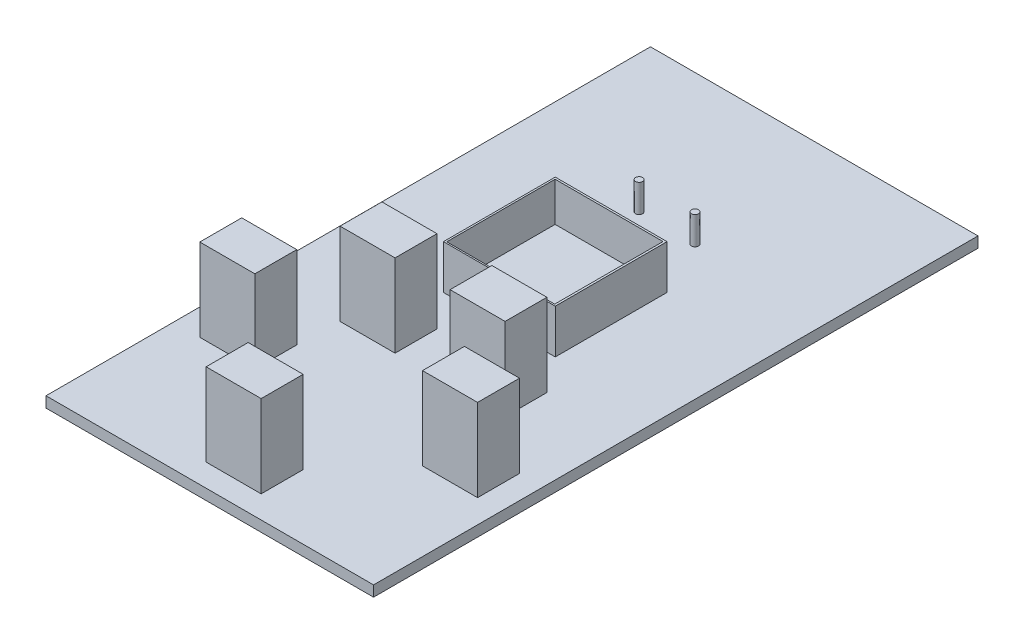
SolidWorks part; units mm, degrees
ref_plane "Front Plane" through (0, 0, 0) normal (0, 0, 1) x (1, 0, 0)
ref_plane "Top Plane" through (0, 0, 0) normal (0, 1, 0) x (1, 0, 0)
ref_plane "Right Plane" through (0, 0, 0) normal (1, 0, 0) x (0, 0, -1)
sketch "Sketch1" plane through (0, 0, 0) normal (0, 1, 0) x (1, 0, 0)
  line L1 (0, 0) -> (101.6, 0)
  line L2 (0, 0) -> (0, 101.6)
  line L3 (0, 101.6) -> (101.6, 101.6)
  line L4 (101.6, 0) -> (101.6, 101.6)
  dimension "D1" = 101.6
  dimension "D2" = 101.6
extrude "Boss-Extrude1" add sketch "Sketch1" along normal blind 39.9999
sketch "Sketch2" plane through (0, 39.9999, 0) normal (0, 1, 0) x (1, 0, 0)
  line L1 (1.6077, 99.8575) -> (99.7228, 99.8575)
  line L2 (1.6077, 99.8575) -> (1.6077, 1.3382)
  line L3 (1.6077, 1.3382) -> (99.7228, 1.3382)
  line L4 (99.7228, 99.8575) -> (99.7228, 1.3382)
extrude "Cut-Extrude1" cut sketch "Sketch2" against normal blind 35.56
sketch "Sketch3" plane through (0, 0, 0) normal (0, -1, 0) x (1, 0, 0)
  line L0 (101.6, -101.6) -> (50.8, -101.6) construction
  line L1 (101.6, -101.6) -> (0, -101.6) construction
  line L2 (50.8, -101.6) -> (50.8, 50.8) construction
  line L3 (50.8, 50.8) -> (25.8, 50.8) construction
  line L4 (50.8, 50.8) -> (75.8, 50.8) construction
  line L5 (25.8, 50.8) -> (25.8, 69.8) construction
  line L6 (75.8, 50.8) -> (75.8, 69.8) construction
  line L7 (50.8, 50.8) -> (50.8, 127) construction
  line L8 (75.8, 69.8) -> (125.7999, 69.8)
  line L9 (75.8, 69.8) -> (75.8, 31.8001)
  line L10 (75.8, 31.8001) -> (125.7999, 31.8001)
  line L11 (125.7999, 69.8) -> (125.7999, 31.8001)
  line L12 (25.8, 69.8) -> (-24.238, 69.8)
  line L13 (25.8, 69.8) -> (25.8, 31.7)
  line L14 (25.8, 31.7) -> (-24.238, 31.7)
  line L15 (-24.238, 69.8) -> (-24.238, 31.7)
  line L16 (50.8, 127) -> (50.8, 203.2) construction
  line L17 (50.8, 127) -> (-25.4, 127) construction
  line L18 (50.8, 127) -> (127, 127) construction
  line L19 (127, 127) -> (127, 146.05) construction
  line L20 (-25.4, 127) -> (-25.4, 146.05) construction
  line L21 (50.8, 203.2) -> (75.692, 203.2) construction
  line L23 (127, 146.05) -> (177.038, 146.05)
  line L24 (127, 146.05) -> (127, 107.95)
  line L25 (127, 107.95) -> (177.038, 107.95)
  line L26 (177.038, 146.05) -> (177.038, 107.95)
  line L27 (-25.4, 146.05) -> (-75.438, 146.05)
  line L28 (-25.4, 146.05) -> (-25.4, 107.95)
  line L29 (-25.4, 107.95) -> (-75.438, 107.95)
  line L30 (-75.438, 146.05) -> (-75.438, 107.95)
  line L35 (75.692, 203.2) -> (25.6473, 203.2)
  line L36 (75.692, 203.2) -> (75.692, 241.4005)
  line L37 (75.692, 241.4005) -> (25.6473, 241.4005)
  line L38 (25.6473, 203.2) -> (25.6473, 241.4005)
  dimension "D1" = 50.8
  dimension "D2" = 152.4
  dimension "D3" = 25
  dimension "D4" = 25
  dimension "D5" = 19
  dimension "D6" = 19
  dimension "D7" = 49.9999
  dimension "D8" = 37.9999
  dimension "D9" = 50.038
  dimension "D10" = 38.1
  dimension "D11" = 76.2
  dimension "D12" = 76.2
  dimension "D13" = 76.2
  dimension "D14" = 76.2
  dimension "D15" = 19.05
  dimension "D16" = 19.05
  dimension "D17" = 24.892
  dimension "D18" = 38.1
  dimension "D19" = 38.1
  dimension "D20" = 50.038
  dimension "D21" = 50.038
  dimension "D22" = 50.0447
  dimension "D23" = 38.2005
extrude "Boss-Extrude2" add sketch "Sketch3" against normal blind 75.0001 separate body
sketch "Sketch4" plane through (0, 0, 0) normal (0, -1, 0) x (1, 0, 0)
  line L1 (-74.296, 144.989) -> (-26.6227, 144.989)
  line L2 (-74.296, 144.989) -> (-74.296, 108.9879)
  line L3 (-74.296, 108.9879) -> (-26.6227, 108.9879)
  line L4 (-26.6227, 144.989) -> (-26.6227, 108.9879)
  line L5 (-22.6945, 68.1578) -> (24.6347, 68.1578)
  line L6 (-22.6945, 68.1578) -> (-22.6945, 32.6665)
  line L7 (-22.6945, 32.6665) -> (24.6347, 32.6665)
  line L8 (24.6347, 68.1578) -> (24.6347, 32.6665)
  line L9 (76.9968, 68.1578) -> (124.3821, 68.1578)
  line L10 (76.9968, 68.1578) -> (76.9968, 33.2532)
  line L11 (76.9968, 33.2532) -> (124.3821, 33.2532)
  line L12 (124.3821, 68.1578) -> (124.3821, 33.2532)
  line L13 (128.504, 144.989) -> (175.9629, 144.989)
  line L14 (128.504, 144.989) -> (128.504, 108.9879)
  line L15 (128.504, 108.9879) -> (175.9629, 108.9879)
  line L16 (175.9629, 144.989) -> (175.9629, 108.9879)
  line L17 (26.5641, 240.2403) -> (74.669, 240.2403)
  line L18 (26.5641, 240.2403) -> (26.5641, 204.2838)
  line L19 (26.5641, 204.2838) -> (74.669, 204.2838)
  line L20 (74.669, 240.2403) -> (74.669, 204.2838)
extrude "Cut-Extrude2" cut sketch "Sketch4" against normal blind 73.2221
sketch "Sketch5" plane through (0, 0, 31.7) normal (0, 0, -1) x (-1, 0, 0)
  line L0 (-0.781, 75.0001) -> (-0.781, 45.0281) construction
  line L1 (24.238, 75.0001) -> (-25.8, 75.0001) construction
  line L2 (-0.781, 45.0281) -> (-0.781, 54.9341) construction
  line L3 (-0.781, 54.9341) -> (-100.8, 54.9341) construction
  circle A0 centre (-0.781, 54.9341) radius 9.906
  circle A1 centre (-100.8, 54.9341) radius 9.9627
  dimension "D3" = 19.9254
  dimension "D1" = 29.972
  dimension "D2" = 9.906
extrude "Cut-Extrude3" cut sketch "Sketch5" against normal blind 9.7221
sketch "Sketch6" plane through (0, 0, 107.95) normal (0, 0, -1) x (-1, 0, 0)
  line L0 (-0.781, 54.9341) -> (50.419, 54.9341) construction
  line L1 (-0.781, 54.9341) -> (-152.019, 54.9341) construction
  circle A0 centre (-152.019, 54.9341) radius 9.906
  circle A1 centre (50.419, 54.9341) radius 9.906
  dimension "D1" = 19.812
  dimension "D2" = 19.812
extrude "Cut-Extrude4" cut sketch "Sketch6" against normal blind 9.7221
sketch "Sketch7" plane through (0, 0, 203.2) normal (0, 0, -1) x (-1, 0, 0)
  line L0 (-100.8, 54.9341) -> (-50.6696, 54.9341) construction
  circle A0 centre (-50.6696, 54.9341) radius 9.906
  dimension "D1" = 19.812
extrude "Cut-Extrude5" cut sketch "Sketch7" against normal blind 9.7221
sketch "Sketch8" plane through (0, 0, 0) normal (0, -1, 0) x (1, 0, 0)
  line L1 (-99.3103, 261.9628) -> (198.4058, 261.9628)
  line L2 (-99.3103, 261.9628) -> (-99.3103, -287.4341)
  line L3 (-99.3103, -287.4341) -> (198.4058, -287.4341)
  line L4 (198.4058, 261.9628) -> (198.4058, -287.4341)
extrude "Boss-Extrude4" add sketch "Sketch8" along normal blind 9.7221 contours L1 L4 L3 L2
sketch "Sketch9" plane through (0, 0, 0) normal (0, 1, 0) x (1, 0, 0)
  line L0 (0, 101.6) -> (50.8, 101.6) construction
  line L1 (101.6, 101.6) -> (0, 101.6) construction
  line L2 (50.8, 101.6) -> (50.8, 152.4) construction
  line L3 (50.8, 152.4) -> (25.4, 152.4) construction
  line L4 (50.8, 152.4) -> (76.2, 152.4) construction
  circle A0 centre (25.4, 152.4) radius 3.175
  circle A1 centre (76.2, 152.4) radius 3.175
  dimension "D3" = 6.35
  dimension "D5" = 6.35
  dimension "D1" = 50.8
  dimension "D2" = 25.4
  dimension "D4" = 25.4
extrude "Boss-Extrude5" add sketch "Sketch9" along normal blind 25.4
